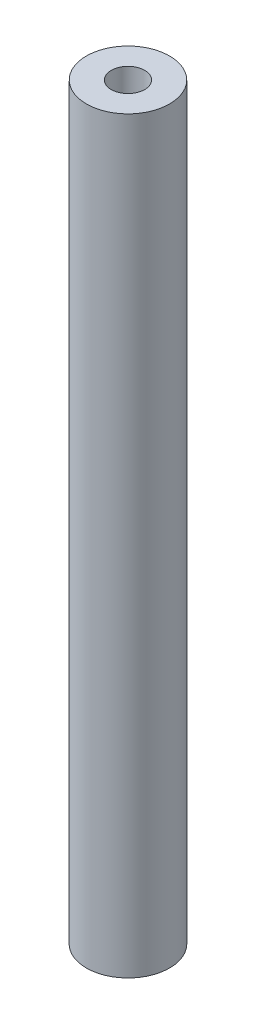
SolidWorks part; units mm, degrees
ref_plane "Front Plane" through (0, 0, 0) normal (0, 0, 1) x (1, 0, 0)
ref_plane "Top Plane" through (0, 0, 0) normal (0, 1, 0) x (1, 0, 0)
ref_plane "Right Plane" through (0, 0, 0) normal (1, 0, 0) x (0, 0, -1)
sketch "Sketch1" plane through (0, 0, 0) normal (0, 1, 0) x (1, 0, 0)
  circle A0 centre (0, 0) radius 6.35
  dimension "D1" = 12.7
extrude "Boss-Extrude1" add sketch "Sketch1" along normal blind 114.3
hole_wizard "1/4-20 Tapped Hole1" positions "Sketch2" profile "Sketch3" tap size "1/4-20" standard "ANSI Inch"
sketch "Sketch2" plane through (0, 114.3, 0) normal (0, 1, 0) x (1, 0, 0)
  point P0 (0, 0)
sketch "Sketch3" plane through (0, 114.3, 0) normal (1, 0, 0) x (0, 0, 1)
  line L0 (0, 0) -> (0, 18.0438)
  line L1 (0, 18.0438) -> (2.5527, 16.51)
  line L2 (2.5527, 16.51) -> (2.5527, 0)
  line L5 (2.5527, 0) -> (0, 0)
  line L10 (0, 18.0438) -> (-2.5527, 16.51) construction
  line L11 (0, -6.35) -> (0, 107.95) construction
  dimension "Tap Drill Dia." = 5.1054
  dimension "Tap Drill Depth" = 16.51
  dimension "Drill Angle" = 118
cosmetic thread "Hole Thread1" parameters "D1"=12.7, "D2"=6.35
